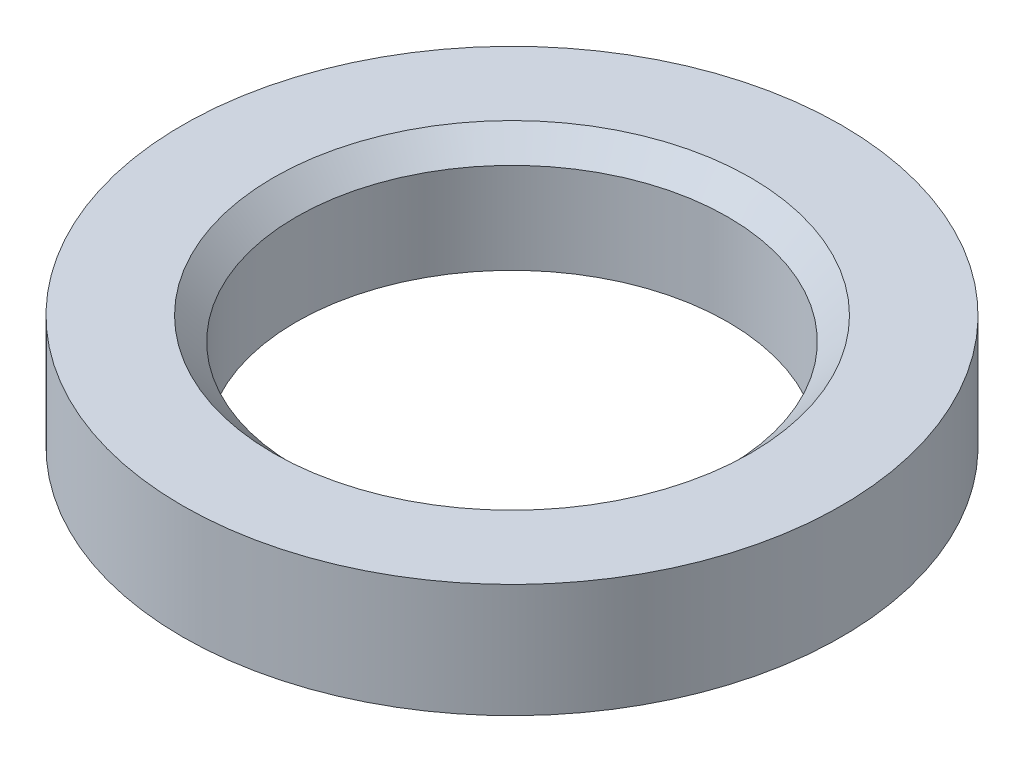
SolidWorks part; units mm, degrees
ref_plane "Front Plane" through (0, 0, 0) normal (0, 0, 1) x (1, 0, 0)
ref_plane "Top Plane" through (0, 0, 0) normal (0, 1, 0) x (1, 0, 0)
ref_plane "Right Plane" through (0, 0, 0) normal (1, 0, 0) x (0, 0, -1)
sketch "Sketch1" plane through (0, 0, 0) normal (0, 0, 1) x (1, 0, 0)
  line L0 (0, 0) -> (0, 28.3207) construction
  line L1 (9.5, 0) -> (14.5, 0)
  line L2 (14.5, 0) -> (14.5, 5)
  line L3 (14.5, 5) -> (10.5, 5)
  line L4 (9.5, 4) -> (9.5, 0)
  line L5 (10.5, 5) -> (9.5, 4)
  point P7 (9.5, 5)
  dimension "D1" = 9.5
  dimension "D2" = 5
  dimension "D3" = 5
revolve "Revolve1" add sketch "Sketch1" angle 360 about L0
